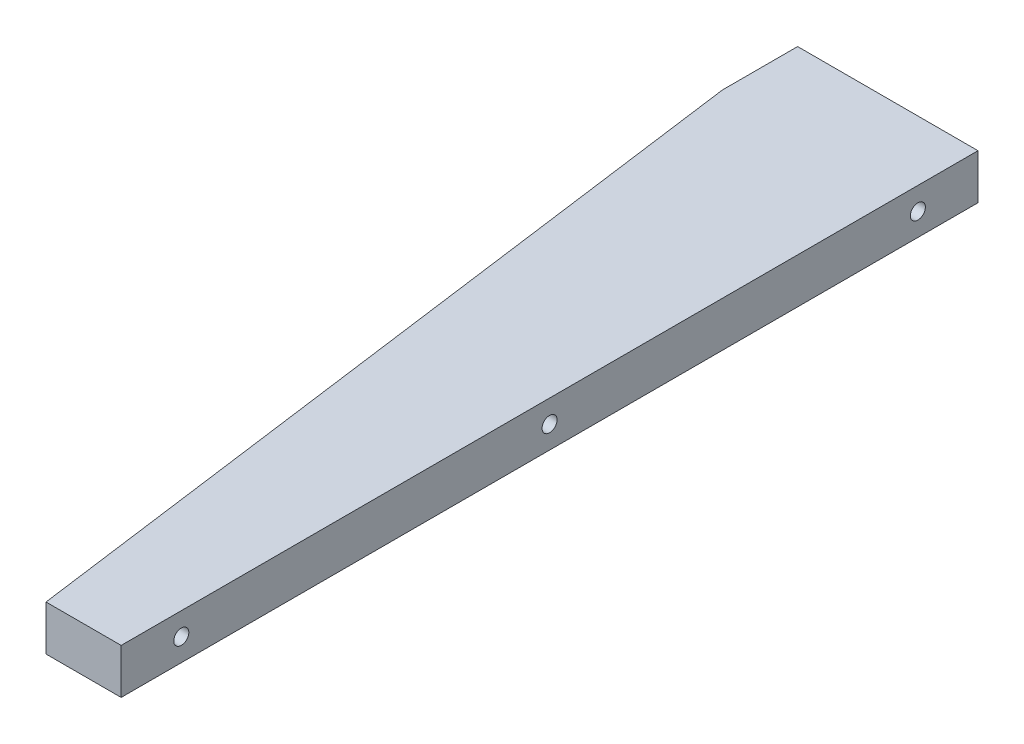
SolidWorks part; units mm, degrees
ref_plane "Front" through (0, 0, 0) normal (0, 0, 1) x (1, 0, 0)
ref_plane "Top" through (0, 0, 0) normal (0, 1, 0) x (1, 0, 0)
ref_plane "Right" through (0, 0, 0) normal (1, 0, 0) x (0, 0, -1)
sketch "Sketch1" plane through (0, 0, 0) normal (0, 1, 0) x (1, 0, 0)
  line L0 (0, 0) -> (0, -285)
  line L1 (0, -285) -> (-25, -285)
  line L2 (-25, -285) -> (-60, -25)
  line L3 (-60, -25) -> (-60, 0)
  line L4 (-60, 0) -> (0, 0)
  dimension "D1" = 60
  dimension "D2" = 285
  dimension "D3" = 25
  dimension "D4" = 25
extrude "Boss-Extrude1" add sketch "Sketch1" along normal blind 15
hole_wizard "M6 Tapped Hole1" positions "Sketch3" profile "Sketch2" tap size "M6" standard "ISO"
sketch "Sketch3" plane through (0, 0, 0) normal (0, 0, -1) x (-1, 0, 0)
  line L0 (0, 15) -> (0, 0) construction
  line L1 (0, 0) -> (60, 0) construction
  point P0 (45, 7.5)
  dimension "D1" = 45
  dimension "D2" = 7.5
sketch "Sketch2" plane through (-45, 7.5, 0) normal (1, 0, 0) x (0, 1, 0)
  line L0 (0, 0) -> (0, 11.5022)
  line L1 (0, 11.5022) -> (2.5, 10)
  line L2 (2.5, 10) -> (2.5, 0)
  line L5 (2.5, 0) -> (0, 0)
  line L10 (0, 11.5022) -> (-2.5, 10) construction
  line L11 (0, -6.35) -> (0, 107.95) construction
  dimension "Tap Drill Dia." = 5
  dimension "Tap Drill Depth" = 10
  dimension "Drill Angle" = 118
cosmetic thread "Hole Thread1" parameters "D1"=7, "D2"=6
hole_wizard "M6 Tapped Hole2" positions "Sketch5" profile "Sketch4" tap size "M6" standard "ISO"
sketch "Sketch5" plane through (0, 0, 0) normal (1, 0, 0) x (0, 0, -1)
  line L0 (0, 15) -> (0, 0) construction
  line L1 (-285, 0) -> (0, 0) construction
  point P0 (-265, 7.5)
  point P1 (-142.5, 7.5)
  point P3 (-20, 7.5)
  dimension "D1" = 20
  dimension "D2" = 122.5
  dimension "D3" = 122.5
  dimension "D4" = 7.5
sketch "Sketch4" plane through (0, 7.5, 265) normal (0, 1, 0) x (0, 0, -1)
  line L0 (0, 0) -> (0, 11.5022)
  line L1 (0, 11.5022) -> (2.5, 10)
  line L2 (2.5, 10) -> (2.5, 0)
  line L5 (2.5, 0) -> (0, 0)
  line L10 (0, 11.5022) -> (-2.5, 10) construction
  line L11 (0, -6.35) -> (0, 107.95) construction
  dimension "Tap Drill Dia." = 5
  dimension "Tap Drill Depth" = 10
  dimension "Drill Angle" = 118
cosmetic thread "Hole Thread2" parameters "D1"=7, "D2"=6
cosmetic thread "Hole Thread3" parameters "D1"=7, "D2"=6
cosmetic thread "Hole Thread4" parameters "D1"=7, "D2"=6
